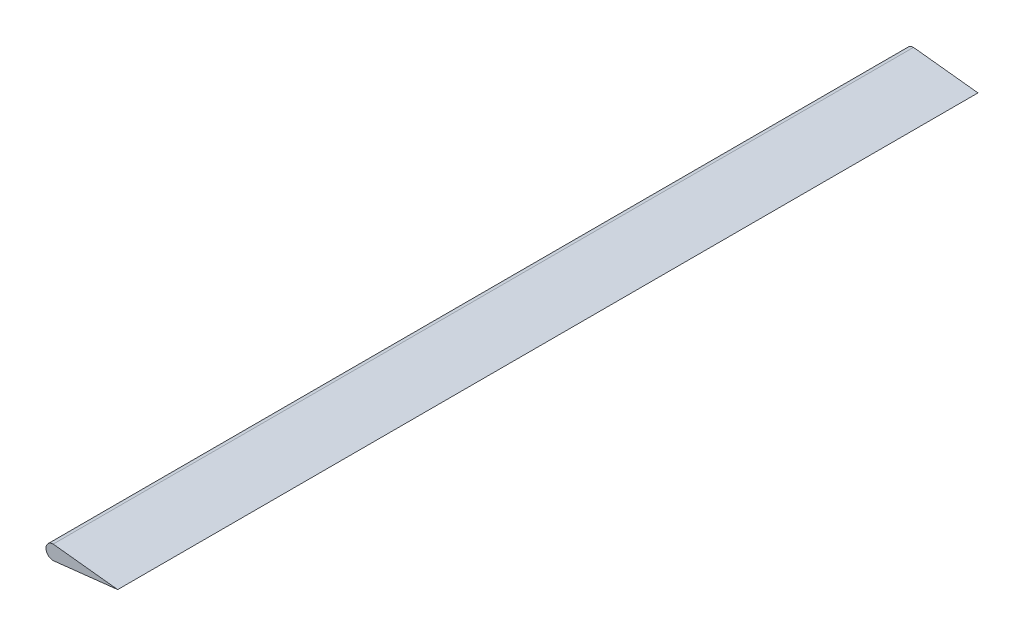
SolidWorks part; units mm, degrees
ref_plane "Front Plane" through (0, 0, 0) normal (0, 0, 1) x (1, 0, 0)
ref_plane "Top Plane" through (0, 0, 0) normal (0, 1, 0) x (1, 0, 0)
ref_plane "Right Plane" through (0, 0, 0) normal (1, 0, 0) x (0, 0, -1)
sketch "Sketch1" plane through (0, 0, 0) normal (0, 0, 1) x (1, 0, 0)
  line L0 (0, 0) -> (1000, 0) construction
  line L7 (100, 100) -> (1000, 0)
  line L8 (1000, 0) -> (100, -100)
  arc A1 (100, 100) -> (100, -100) centre (100, 0) ccw
  dimension "D1" = 1000
  dimension "D2" = 200
extrude "Boss-Extrude1" add sketch "Sketch1" along normal blind 12000 contours L7 L8 A1
